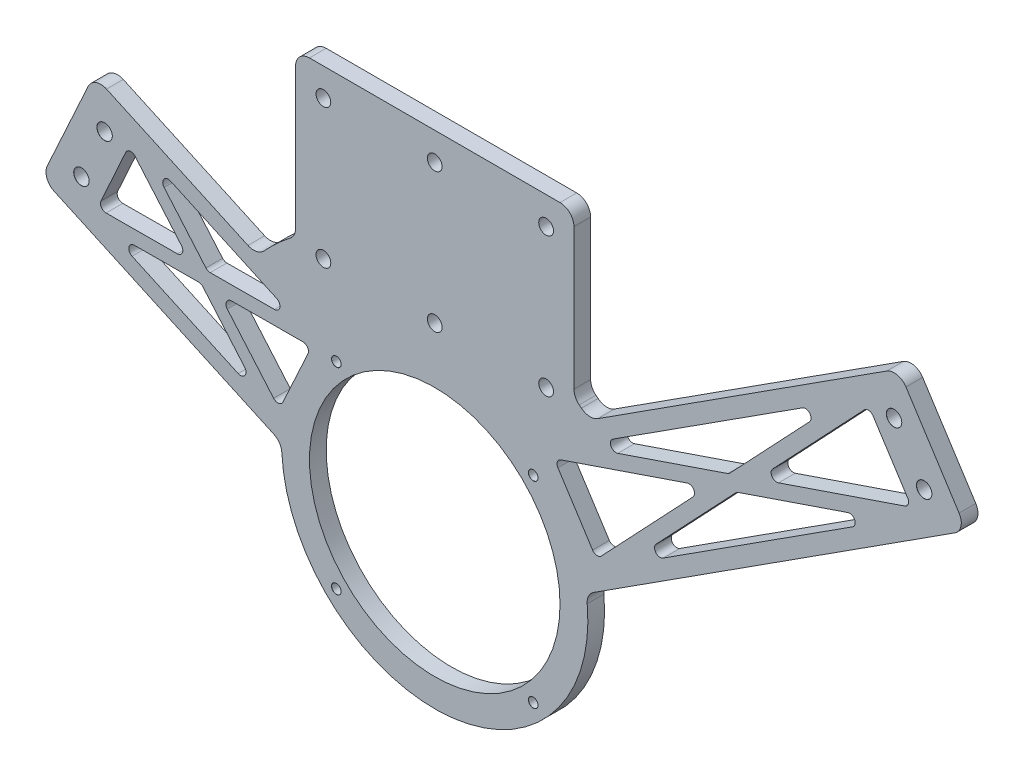
SolidWorks part; units mm, degrees
ref_plane "Front" through (0, 0, 0) normal (0, 0, 1) x (1, 0, 0)
ref_plane "Top" through (0, 0, 0) normal (0, 1, 0) x (1, 0, 0)
ref_plane "Right" through (0, 0, 0) normal (1, 0, 0) x (0, 0, -1)
sketch "Body Driving Dimensions" plane through (0, 0, 0) normal (0, 0, 1) x (1, 0, 0)
  line L0 (0, 0) -> (55.1074, -64.7161)
  line L1 (55.1074, -64.7161) -> (0, -241.3179)
  line L2 (0, -241.3179) -> (-55.1074, -64.7161)
  line L3 (-55.1074, -64.7161) -> (0, 0)
  line L4 (0, 0) -> (0, -36.971) construction
  line L5 (0, 0) -> (153.5661, 98.7013)
  line L6 (153.5661, 98.7013) -> (55.1074, -64.7161)
  line L7 (0, 0) -> (-104.5705, 47.854)
  line L8 (-104.5705, 47.854) -> (-55.1074, -64.7161)
  line L9 (153.5661, 98.7013) -> (256.2032, 164.669) construction
  line L10 (-104.5705, 47.854) -> (-215.514, 98.6245) construction
  line L11 (153.5661, 98.7013) -> (153.5661, 67.0292) construction
  line L12 (-104.5705, 47.854) -> (-104.5705, 16.182) construction
  line L13 (0, 0) -> (-98.8336, -98.8336) construction
  line L14 (0, 0) -> (98.8336, -98.8336) construction
  line L15 (-126.9179, 47.0834) -> (-118.5955, 65.2696)
  line L16 (175.7975, 101.1026) -> (164.9839, 117.9272)
  point P16 (-122.7567, 56.1765)
  point P20 (170.3907, 109.5149)
  dimension "D1" = 45
  dimension "D2" = 45
  dimension "D3" = 185
  dimension "D4" = 85
  dimension "D5" = 182.55
  dimension "D6" = 115
  dimension "D7" = 122.73
  dimension "D8" = 114.59
  dimension "D9" = 20
  dimension "D10" = 20
  dimension "D11" = 20
  dimension "D12" = 20
sketch "Sketch6" plane through (0, 0, 0) normal (0, 0, 1) x (1, 0, 0)
  line L0 (-33.3042, 78.2038) -> (-104.5705, 47.854) construction
  line L1 (-7.3776, 84.6792) -> (153.5661, 98.7013) construction
  circle A0 centre (0, 0) radius 85 construction
  circle A1 centre (0, 0) radius 182.55 construction
  circle A2 centre (0, 0) radius 115 construction
sketch "Sketch8" plane through (0, 0, 0) normal (0, 0, 1) x (1, 0, 0)
  line L0 (0, 0) -> (0, 150) construction
  line L3 (0, 150) -> (0, 115) construction
  line L4 (0, 0) -> (-128.3471, 58.7348) construction
  line L7 (0, 0) -> (-104.5705, 47.854) construction
  line L8 (-104.5705, 47.854) -> (-215.514, 98.6245) construction
  line L12 (40, 115) -> (-40, 115) construction
  line L13 (40, 65) -> (-40, 65) construction
  line L14 (-141.2749, 39.7419) -> (-122.4246, 80.9335)
  line L15 (-122.4246, 80.9335) -> (-63.7414, 54.0787)
  line L16 (0, 0) -> (182.2103, 117.1117) construction
  line L17 (-141.2749, 39.7419) -> (-54.9994, 0.26)
  line L18 (-50, 66.9886) -> (-50, 125)
  line L19 (-50, 125) -> (50, 125)
  line L20 (50, 125) -> (50, 66.9886)
  line L21 (191.0494, 95.8679) -> (54.4084, 8.0449)
  line L23 (153.5661, 98.7013) -> (256.2032, 164.669) construction
  line L24 (191.0494, 95.8679) -> (166.5565, 133.9755)
  line L25 (166.5565, 133.9755) -> (55.4421, 62.5591)
  line L26 (175.7975, 101.1026) -> (164.9839, 117.9272) construction
  circle A0 centre (0, 0) radius 55 construction
  circle A1 centre (0, 0) radius 182.55 construction
  circle A2 centre (0, 0) radius 45
  circle A4 centre (-40, 115) radius 2.65
  circle A5 centre (0, 0) radius 115 construction
  circle A6 centre (40, 115) radius 2.65
  circle A7 centre (0, 115) radius 2.65
  circle A8 centre (40, 65) radius 2.65
  circle A9 centre (0, 65) radius 2.65
  circle A10 centre (-40, 65) radius 2.65
  circle A11 centre (0, 0) radius 83.5911 construction
  arc A12 (-63.7414, 54.0787) -> (-50, 66.9886) centre (0, 0) cw
  arc A13 (-54.9994, 0.26) -> (54.4084, 8.0449) centre (0, 0) ccw
  arc A14 (50, 66.9886) -> (55.4421, 62.5591) centre (0, 0) cw
  point P12 (0, 182.55)
  point P17 (-131.8498, 60.3377)
  point P26 (0, 115)
  point P37 (0, 65)
  point P50 (178.803, 114.9217)
  dimension "D2" = 110
  dimension "D3" = 90
  dimension "D10" = 5.3
  dimension "D16" = 40
  dimension "D4" = 65
  dimension "D5" = 45.3
  dimension "D6" = 10
  dimension "D7" = 45.3
  dimension "D8" = 10
  dimension "D9" = 10
  dimension "D11" = 80
  dimension "D12" = 50
  dimension "D13" = 35
  dimension "D14" = 10
  dimension "D15" = 10
extrude "Boss-Extrude12" add sketch "Sketch8" along normal blind 6 contours A14 L20 L19 L18 A12 L15 L14 L17 A13 L21 L24 L25 A10 A9 A8 A7 A6 A4 A2
hole_wizard "M5 Clearance Hole3" positions "Sketch39" profile "Sketch40" hole size "M5" standard "ANSI Metric" end condition through all
sketch "Sketch39" plane through (0, 0, 6) normal (0, 0, 1) x (1, 0, 0)
  point P0 (-118.5955, 65.2696)
  point P3 (-126.9179, 47.0834)
  point P6 (164.9839, 117.9272)
  point P9 (175.7975, 101.1026)
sketch "Sketch40" plane through (-118.5955, 65.2696, 6) normal (1, 0, 0) x (0, -1, 0)
  line L0 (0, 0) -> (0, 6)
  line L1 (0, 6) -> (2.75, 6)
  line L2 (2.75, 6) -> (2.75, 0.025)
  line L3 (2.75, 0.025) -> (2.775, 0)
  line L5 (2.775, 0) -> (0, 0)
  line L6 (-2.75, 0.025) -> (-2.775, 0) construction
  line L11 (0, -6.35) -> (0, 107.95) construction
  dimension "Thru Hole Dia." = 5.5
  dimension "Thru Hole Depth" = 6
  dimension "Near C'Sink Dia." = 5.55
  dimension "Near C'Sink Angle" = 90
sketch "Sketch41" plane through (0, 0, 6) normal (0, 0, 1) x (1, 0, 0)
  line L0 (0, -45) -> (0, 45) construction
  line L1 (0, 0) -> (35.3553, 35.3553) construction
  line L2 (0, 0) -> (35.3553, -35.3553) construction
  circle A0 centre (0, 0) radius 50 construction
  circle A1 centre (0, 0) radius 45 construction
  point P10 (-35.3553, -35.3553)
  point P11 (35.3553, -35.3553)
  point P12 (35.3553, 35.3553)
  point P13 (-35.3553, 35.3553)
  dimension "D1" = 100
  dimension "D2" = 45
  dimension "D3" = 45
hole_wizard "M3 Clearance Hole2" positions "Sketch42" profile "Sketch43" hole size "M3" standard "ANSI Metric" end condition through all
sketch "Sketch42" plane through (0, 0, 6) normal (0, 0, 1) x (1, 0, 0)
  point P0 (-35.3553, 35.3553)
  point P3 (35.3553, 35.3553)
  point P6 (35.3553, -35.3553)
  point P9 (-35.3553, -35.3553)
sketch "Sketch43" plane through (-35.3553, 35.3553, 6) normal (1, 0, 0) x (0, -1, 0)
  line L0 (0, 0) -> (0, 6)
  line L1 (0, 6) -> (1.7, 6)
  line L2 (1.7, 6) -> (1.7, 0.025)
  line L3 (1.7, 0.025) -> (1.725, 0)
  line L5 (1.725, 0) -> (0, 0)
  line L6 (-1.7, 0.025) -> (-1.725, 0) construction
  line L11 (0, -6.35) -> (0, 107.95) construction
  dimension "Thru Hole Dia." = 3.4
  dimension "Thru Hole Depth" = 6
  dimension "Near C'Sink Dia." = 3.45
  dimension "Near C'Sink Angle" = 90
sketch "Sketch45" plane through (0, 0, 6) normal (0, 0, 1) x (1, 0, 0)
  line L4 (-56.9404, 7.7467) -> (-43.0835, 38.0267) construction
  line L6 (-82.7471, 37.8671) -> (-89.6755, 22.7271) construction
  line L7 (-116.9952, 35.2293) -> (-62.3558, 10.225)
  line L8 (-62.3558, 10.225) -> (-83.8933, 35.3625)
  line L9 (-83.8933, 35.3625) -> (-116.9952, 35.2293)
  line L10 (59.476, 18.4344) -> (41.4713, 46.4473) construction
  line L11 (59.476, 18.4344) -> (172.6632, 91.183) construction
  line L12 (41.4713, 46.4473) -> (154.6585, 119.1959) construction
  line L13 (172.6632, 91.183) -> (154.6585, 119.1959) construction
  line L14 (59.476, 18.4344) -> (154.6585, 119.1959) construction
  line L15 (41.4713, 46.4473) -> (172.6632, 91.183) construction
  line L16 (0, 0) -> (153.5661, 98.7013) construction
  line L17 (175.7975, 101.1026) -> (164.9839, 117.9272) construction
  line L18 (166.5565, 133.9755) -> (55.4421, 62.5591) construction
  line L19 (191.0494, 95.8679) -> (54.4084, 8.0449) construction
  line L32 (-56.9404, 7.7467) -> (-122.4106, 37.7075) construction
  line L33 (-43.0835, 38.0267) -> (-108.5538, 67.9875) construction
  line L34 (-122.4106, 37.7075) -> (-108.5538, 67.9875) construction
  line L35 (-56.9404, 7.7467) -> (-108.5538, 67.9875) construction
  line L36 (-43.0835, 38.0267) -> (-122.4106, 37.7075) construction
  line L37 (0, 0) -> (-104.5705, 47.854) construction
  line L38 (-122.4246, 80.9335) -> (-63.7414, 54.0787) construction
  line L39 (-50.012, 22.8867) -> (-115.4822, 52.8475) construction
  line L40 (-81.6009, 40.3717) -> (-103.1384, 65.5093)
  line L41 (-103.1384, 65.5093) -> (-48.499, 40.5049)
  line L42 (-48.499, 40.5049) -> (-81.6009, 40.3717)
  line L43 (-55.8486, 10.3148) -> (-44.2297, 35.5221)
  line L44 (-44.2297, 35.5221) -> (-77.3317, 35.3889)
  line L45 (-77.3317, 35.3889) -> (-55.8486, 10.3148)
  line L46 (-109.7, 65.4829) -> (-88.1625, 40.3453)
  line L47 (-121.1809, 40.2125) -> (-109.7, 65.4829)
  line L48 (-88.1625, 40.3453) -> (-121.1809, 40.2125)
  line L49 (50.4737, 32.4409) -> (163.6609, 105.1895) construction
  line L50 (116.0696, 54.8087) -> (98.0649, 82.8216) construction
  line L51 (42.8638, 44.2808) -> (58.0835, 20.6009)
  line L52 (58.0835, 20.6009) -> (98.3134, 63.1888)
  line L53 (98.3134, 63.1888) -> (42.8638, 44.2808)
  line L54 (171.2707, 93.3495) -> (115.8212, 74.4415)
  line L55 (156.051, 117.0294) -> (171.2707, 93.3495)
  line L56 (115.8212, 74.4415) -> (156.051, 117.0294)
  line L57 (68.2299, 24.0608) -> (163.9093, 85.5566)
  line L58 (163.9093, 85.5566) -> (108.4598, 66.6486)
  line L59 (108.4598, 66.6486) -> (68.2299, 24.0608)
  line L60 (145.9046, 113.5695) -> (105.6748, 70.9817)
  line L61 (50.2252, 52.0737) -> (145.9046, 113.5695)
  line L62 (105.6748, 70.9817) -> (50.2252, 52.0737)
  point P1 (-82.7471, 37.8671)
  point P16 (107.0673, 68.8152)
  point P28 (-89.6755, 22.7271)
  point P37 (-50.0392, 22.9184)
  point P49 (50.4737, 32.4409)
  point P56 (116.0696, 54.8087)
  dimension "D1" = 6
  dimension "D2" = 8
  dimension "D3" = 55
  dimension "D4" = 8
  dimension "D5" = 6
  dimension "D6" = 6
  dimension "D7" = 60
  dimension "D8" = 2.5
  dimension "D9" = 2.5
  dimension "D10" = 2.5
  dimension "D11" = 2.5
extrude "Cut-Extrude12" cut sketch "Sketch45" against normal through all
fillet "Fillet16" radius 2 12 edges at (-77.3317, 35.3889, 3) (-44.2297, 35.5221, 3) (-55.8486, 10.3148, 3) (-116.9952, 35.2293, 3) (-62.3558, 10.225, 3) (-83.8933, 35.3625, 3) (-109.7, 65.4829, 3) (-121.1809, 40.2125, 3) (-88.1625, 40.3453, 3) (-48.499, 40.5049, 3) (-81.6009, 40.3717, 3) (-103.1384, 65.5093, 3)
fillet "Fillet17" radius 2 12 edges at (163.9093, 85.5566, 3) (58.0835, 20.6009, 3) (42.8638, 44.2808, 3) (68.2299, 24.0608, 3) (98.3134, 63.1888, 3) (50.2252, 52.0737, 3) (156.051, 117.0294, 3) (108.4598, 66.6486, 3) (115.8212, 74.4415, 3) (171.2707, 93.3495, 3) (105.6748, 70.9817, 3) (145.9046, 113.5695, 3)
fillet "Fillet13" radius 5 12 edges at (-50, 125, 3) (-50, 66.9886, 3) (-63.7414, 54.0787, 3) (-122.4246, 80.9335, 3) (-141.2749, 39.7419, 3) (-54.9994, 0.26, 3) (54.4084, 8.0449, 3) (191.0494, 95.8679, 3) (166.5565, 133.9755, 3) (55.4421, 62.5591, 3) (50, 66.9886, 3) (50, 125, 3)
sketch "Sketch17" [suppressed] plane through (0, 0, 0) normal (0, 0, 1) x (1, 0, 0)
  line L0 (0, 0) -> (-45, 0) construction
  line L1 (0, 0) -> (0, 45) construction
  line L2 (0, 0) -> (-35.3553, 35.3553) construction
  line L3 (0, 0) -> (0, 170) construction
  line L4 (54, 170) -> (-54, 170)
  line L5 (-54, 170) -> (-54, 0)
  line L6 (54, 0) -> (54, 170)
  line L7 (45, 162.5) -> (-45, 162.5) construction
  line L8 (45, 112.5) -> (-45, 112.5) construction
  circle A0 centre (0, 0) radius 45
  circle A1 centre (-35.3553, 35.3553) radius 1.65
  circle A2 centre (35.3553, 35.3553) radius 1.65
  circle A3 centre (35.3553, -35.3553) radius 1.65
  circle A4 centre (-35.3553, -35.3553) radius 1.65
  circle A5 centre (0, 0) radius 54 construction
  circle A6 centre (0, 162.5) radius 2.65
  arc A7 (-54, 0) -> (54, 0) centre (0, 0) ccw
  circle A8 centre (-45, 162.5) radius 2.65
  circle A9 centre (45, 162.5) radius 2.65
  circle A10 centre (-45, 112.5) radius 2.65
  circle A11 centre (-35.3553, 35.3553) radius 4 construction
  circle A12 centre (0, 112.5) radius 2.65
  circle A13 centre (45, 112.5) radius 2.65
  point P16 (0, 0)
  point P19 (0, 170)
  point P25 (0, 162.5)
  point P33 (0, 112.5)
  dimension "D1" = 90
  dimension "D4" = 3.3
  dimension "D6" = 170
  dimension "D9" = 5.3
  dimension "D11" = 8
  dimension "D7" = 50
  dimension "D2" = 45
  dimension "D3" = 50
  dimension "D8" = 90
  dimension "D10" = 7.5
  dimension "D5" = 4
extrude "Simple Side Plate" [suppressed] add sketch "Sketch17" along normal blind 6
fillet "Fillet7" [suppressed] radius 2.5
sketch "Sketch44" [suppressed] plane through (0, 0, 6) normal (0, 0, 1) x (1, 0, 0)
  line L0 (-65.2013, 13.7266) -> (-53.0089, 40.3693)
  line L1 (-65.2013, 13.7266) -> (-115.2132, 36.6133)
  line L2 (-53.0089, 40.3693) -> (-103.0209, 63.256)
  line L3 (-115.2132, 36.6133) -> (-103.0209, 63.256)
  line L4 (-65.2013, 13.7266) -> (-103.0209, 63.256) construction
  line L5 (-53.0089, 40.3693) -> (-115.2132, 36.6133) construction
  line L6 (0, 0) -> (-100.024, 45.7734) construction
  line L7 (-117.8781, 78.8529) -> (-63.7414, 54.0787) construction
  line L8 (77.023, 48.4736) -> (68.633, 61.5274)
  line L13 (77.023, 48.4736) -> (135.2836, 85.9194)
  line L14 (68.633, 61.5274) -> (126.8936, 98.9731)
  line L17 (135.2836, 85.9194) -> (126.8936, 98.9731)
  line L18 (77.023, 48.4736) -> (126.8936, 98.9731) construction
  line L19 (68.633, 61.5274) -> (135.2836, 85.9194) construction
  line L20 (0, 0) -> (149.36, 95.9979) construction
  line L21 (162.3504, 131.2721) -> (55.4421, 62.5591) construction
  circle A0 centre (-122.3714, 45.0028) radius 2.775 construction
  point P1 (-84.1111, 38.4913)
  point P12 (101.9583, 73.7234)
  dimension "D1" = 10
  dimension "D2" = 8
  dimension "D3" = 57.5
  dimension "D4" = 8
extrude "Cut-Extrude11" [suppressed] cut sketch "Sketch44" against normal blind 81
equation "\"l2\"= 185"
equation "\"D3@Body Driving Dimensions\" = \"l2\""
equation "\"l1\"= 85"
equation "\"D4@Body Driving Dimensions\" = \"l1\""
equation "\"s1r\"= 2.14212rad"
equation "\"s2r\"= - 2rad"
equation "\"offset\" = 15mm"
equation "\"s1_len\"= 0.08255m"
equation "\"s2_len\"= 0.015m"
equation "\"s1_anchor_dist\"= \"offset\" + \"l1\" + \"s1_len\""
equation "\"s2_anchor_dist\"= \"offset\" + \"l1\" + \"s2_len\"'this was: = \"offset\" + \"l1\" + \"s2_len\""
equation "\"D5@Body Driving Dimensions\" = \"s1_anchor_dist\""
equation "\"D6@Body Driving Dimensions\" = \"s2_anchor_dist\""
equation "\"D7@Body Driving Dimensions\" = \"s1r\""
equation "\"D8@Body Driving Dimensions\" =  - \"s2r\""
equation "\"carbon_fiber_plate_thickness\"=6"
equation "\"motor_to_motor_spacing\"=55.5"
equation "\"D1\" = \"motor_to_motor_spacing\" + 30mm"
equation "\"D1@Boss-Extrude12\"=\"carbon_fiber_plate_thickness\""
equation "\"D3@Sketch44\"=\"s2_anchor_dist\"/2"
